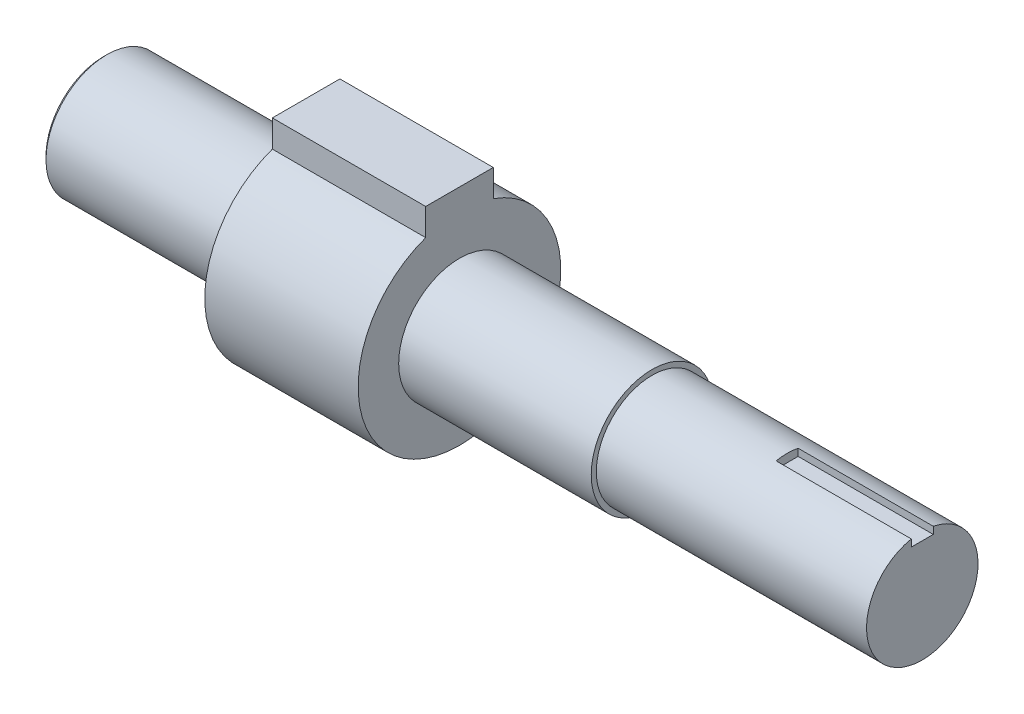
SolidWorks part; units mm, degrees
ref_plane "Front Plane" through (0, 0, 0) normal (0, 0, 1) x (1, 0, 0)
ref_plane "Top Plane" through (0, 0, 0) normal (0, 1, 0) x (1, 0, 0)
ref_plane "Right Plane" through (0, 0, 0) normal (1, 0, 0) x (0, 0, -1)
sketch "Sketch1" plane through (0, 0, 0) normal (0, 0, 1) x (1, 0, 0)
  line L1 (0, 0) -> (30, 0)
  line L2 (0, 0) -> (0, 9)
  line L3 (0, 9) -> (30, 9)
  line L4 (30, 0) -> (30, 9)
  dimension "D1" = 30
  dimension "D2" = 9
revolve "Revolve1" add sketch "Sketch1" angle 360 about L1
sketch "Sketch2" plane through (30, 0, 0) normal (1, 0, 0) x (0, 0, -1)
  line L0 (-5, 18.1421) -> (5, 18.1421)
  line L1 (5, 18.1421) -> (5, 14.1421)
  line L2 (-5, 18.1421) -> (-5, 14.1421)
  line L3 (0, 0) -> (0, 15) construction
  arc A0 (-5, 14.1421) -> (5, 14.1421) centre (0, 0) ccw
  dimension "D1" = 30
  dimension "D2" = 10
  dimension "D3" = 4
  dimension "D4" = 5
extrude "Boss-Extrude1" add sketch "Sketch2" along normal blind 22.7
sketch "Sketch3" plane through (52.7, 0, 0) normal (1, 0, 0) x (0, 0, -1)
  circle A0 centre (0, 0) radius 9 construction
  circle A1 centre (0, 0) radius 9
extrude "Boss-Extrude2" add sketch "Sketch3" along normal blind 28.5
sketch "Sketch4" plane through (81.2, 0, 0) normal (1, 0, 0) x (0, 0, -1)
  circle A0 centre (0, 0) radius 8.25
  dimension "D1" = 16.5
extrude "Boss-Extrude3" add sketch "Sketch4" along normal blind 40
sketch "Sketch5" plane through (121.2, 0, 0) normal (1, 0, 0) x (0, 0, -1)
  line L0 (0, 0) -> (0, 13.2375) construction
  line L1 (-1.625, 7.04) -> (1.625, 8.54) construction
  line L2 (-1.625, 8.54) -> (1.625, 8.54)
  line L3 (-1.625, 8.54) -> (-1.625, 7.04)
  line L4 (-1.625, 7.04) -> (1.625, 7.04)
  line L5 (1.625, 8.54) -> (1.625, 7.04)
  line L6 (-1.625, 8.54) -> (1.625, 7.04) construction
  point P7 (0, 7.79)
  dimension "D1" = 3.25
  dimension "D2" = 1.5
  dimension "D3" = 7.04
extrude "Cut-Extrude1" cut sketch "Sketch5" against normal blind 20
chamfer "Chamfer1" distance 0.5 angle 45 1 edges at (0, 0, 9)
